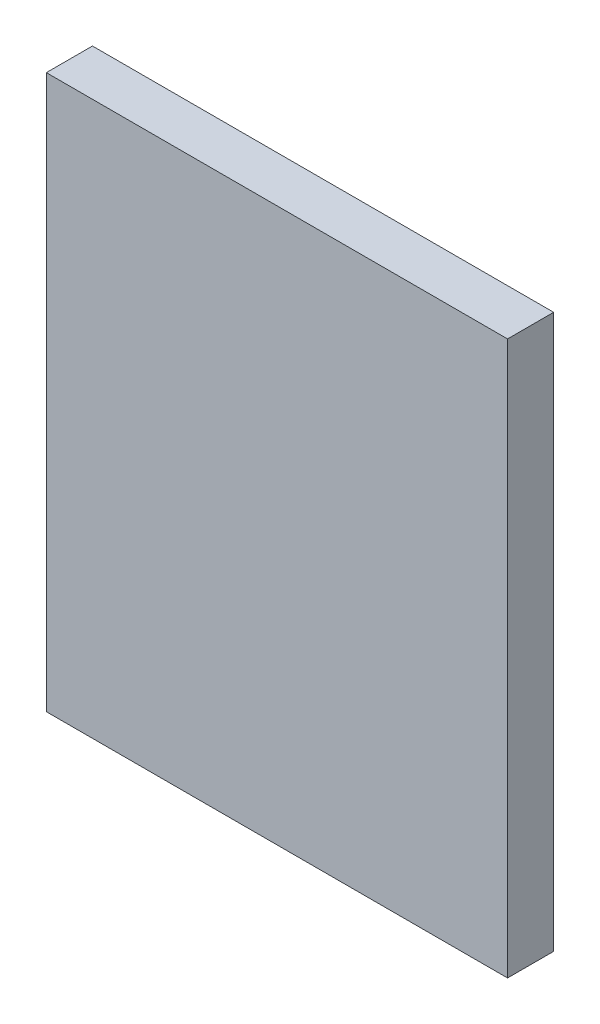
SolidWorks part; units mm, degrees
ref_plane "前视基准面" through (0, 0, 0) normal (0, 0, 1) x (1, 0, 0)
ref_plane "上视基准面" through (0, 0, 0) normal (0, 1, 0) x (1, 0, 0)
ref_plane "右视基准面" through (0, 0, 0) normal (1, 0, 0) x (0, 0, -1)
ref_plane "基准面1" through (0, 0, 5) normal (0, 0, 1) x (1, 0, 0)
sketch "草图1" plane through (0, 0, 5) normal (0, 0, 1) x (1, 0, 0)
  line L0 (0, 60) -> (0, 0)
  line L1 (0, 0) -> (50, 0)
  line L2 (50, 0) -> (50, 60)
  line L3 (50, 60) -> (0, 60)
extrude "凸台-拉伸1" add sketch "草图1" against normal blind 5
